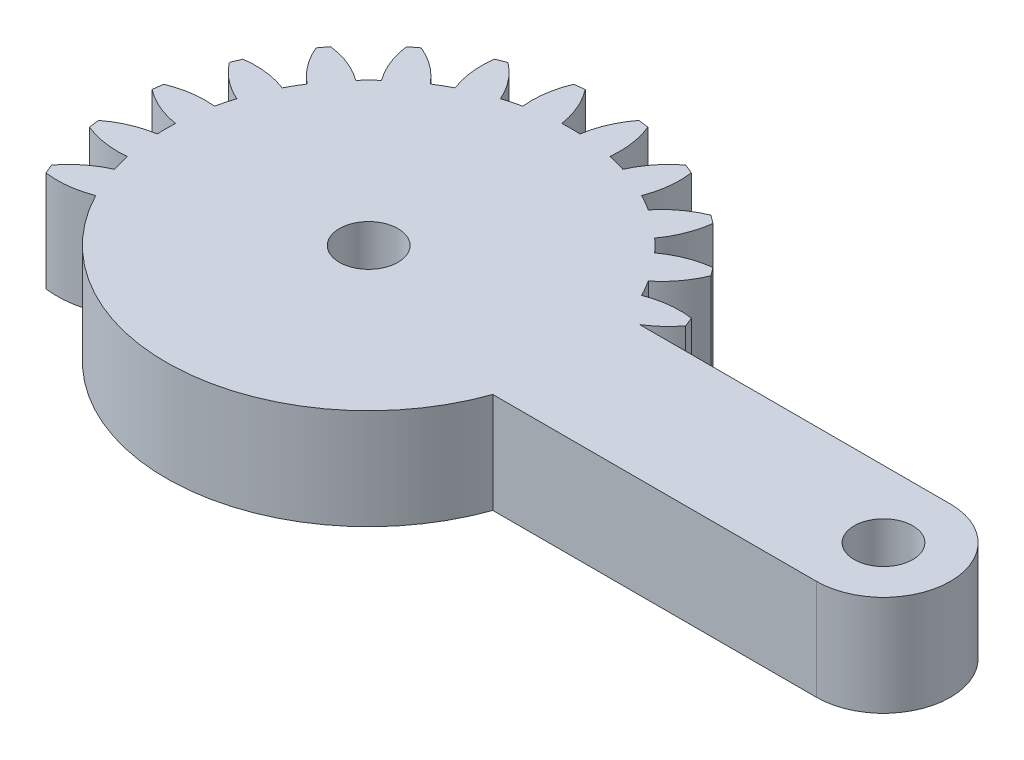
SolidWorks part; units mm, degrees
ref_plane "Front Plane" through (0, 0, 0) normal (0, 0, 1) x (1, 0, 0)
ref_plane "Top Plane" through (0, 0, 0) normal (0, 1, 0) x (1, 0, 0)
ref_plane "Right Plane" through (0, 0, 0) normal (1, 0, 0) x (0, 0, -1)
sketch "Sketch1" plane through (0, 0, 0) normal (0, 1, 0) x (1, 0, 0)
  line L0 (20.6437, 4) -> (2.0816, 4)
  line L1 (2.0816, -4) -> (20.6437, -4)
  arc A0 (2.0816, 4) -> (3.5217, 5.3071) centre (-0.7683, 8.5867) ccw
  arc A1 (3.5217, 5.3071) -> (3.2829, 5.8838) centre (-10.1063, 0) ccw
  arc A2 (3.2829, 5.8838) -> (0.6271, 5.5703) centre (2.5684, 0.5313) ccw
  arc A3 (0.6271, 5.5703) -> (0.0844, 6.5103) centre (-10.1063, 0) ccw
  arc A4 (0.0844, 6.5103) -> (1.6838, 8.6535) centre (-3.3089, 10.711) ccw
  arc A5 (1.6838, 8.6535) -> (1.3038, 9.1487) centre (-10.1063, 0) ccw
  arc A6 (1.3038, 9.1487) -> (-1.1803, 8.1585) centre (1.999, 3.7936) ccw
  arc A7 (-1.1803, 8.1585) -> (-1.9479, 8.926) centre (-10.1063, 0) ccw
  arc A8 (-1.9479, 8.926) -> (-0.9576, 11.4102) centre (-6.3127, 12.1053) ccw
  arc A9 (-0.9576, 11.4102) -> (-1.4528, 11.7901) centre (-10.1063, 0) ccw
  arc A10 (-1.4528, 11.7901) -> (-3.596, 10.1907) centre (0.6046, 6.7975) ccw
  arc A11 (-3.596, 10.1907) -> (-4.5361, 10.7334) centre (-10.1063, 0) ccw
  arc A12 (-4.5361, 10.7334) -> (-4.2225, 13.3892) centre (-9.5751, 12.6747) ccw
  arc A13 (-4.2225, 13.3892) -> (-4.7992, 13.6281) centre (-10.1063, 0) ccw
  arc A14 (-4.7992, 13.6281) -> (-6.4554, 11.5285) centre (-1.5196, 9.3381) ccw
  arc A15 (-6.4554, 11.5285) -> (-7.5039, 11.8094) centre (-10.1063, 0) ccw
  arc A16 (-7.5039, 11.8094) -> (-7.8884, 14.4558) centre (-12.8736, 12.3803) ccw
  arc A17 (-7.8884, 14.4558) -> (-8.5072, 14.5373) centre (-10.1063, 0) ccw
  arc A18 (-8.5072, 14.5373) -> (-9.5636, 12.0806) centre (-4.2291, 11.2423) ccw
  arc A19 (-9.5636, 12.0806) -> (-10.6491, 12.0806) centre (-10.1063, 0) ccw
  arc A20 (-10.6491, 12.0806) -> (-11.7054, 14.5373) centre (-15.9836, 11.2423) ccw
  arc A21 (-11.7054, 14.5373) -> (-12.3243, 14.4558) centre (-10.1063, 0) ccw
  arc A22 (-12.3243, 14.4558) -> (-12.7088, 11.8094) centre (-7.3391, 12.3803) ccw
  arc A23 (-12.7088, 11.8094) -> (-13.7573, 11.5285) centre (-10.1063, 0) ccw
  arc A24 (-13.7573, 11.5285) -> (-15.4135, 13.6281) centre (-18.6931, 9.3381) ccw
  arc A25 (-15.4135, 13.6281) -> (-15.9901, 13.3892) centre (-10.1063, 0) ccw
  arc A26 (-15.9901, 13.3892) -> (-15.6766, 10.7334) centre (-10.6376, 12.6747) ccw
  arc A27 (-15.6766, 10.7334) -> (-16.6166, 10.1907) centre (-10.1063, 0) ccw
  arc A28 (-16.6166, 10.1907) -> (-18.7599, 11.7901) centre (-20.8173, 6.7975) ccw
  arc A29 (-18.7599, 11.7901) -> (-19.255, 11.4102) centre (-10.1063, 0) ccw
  arc A30 (-19.255, 11.4102) -> (-18.2648, 8.926) centre (-13.9, 12.1053) ccw
  arc A31 (-18.2648, 8.926) -> (-19.0324, 8.1585) centre (-10.1063, 0) ccw
  arc A32 (-19.0324, 8.1585) -> (-21.5165, 9.1487) centre (-22.2117, 3.7936) ccw
  arc A33 (-21.5165, 9.1487) -> (-21.8965, 8.6535) centre (-10.1063, 0) ccw
  arc A34 (-21.8965, 8.6535) -> (-20.2971, 6.5103) centre (-16.9038, 10.711) ccw
  arc A35 (-20.2971, 6.5103) -> (-20.8398, 5.5703) centre (-10.1063, 0) ccw
  arc A36 (-20.8398, 5.5703) -> (-23.4956, 5.8838) centre (-22.7811, 0.5313) ccw
  arc A37 (-23.4956, 5.8838) -> (-23.7344, 5.3071) centre (-10.1063, 0) ccw
  arc A38 (-23.7344, 5.3071) -> (-21.6348, 3.6509) centre (-19.4444, 8.5867) ccw
  arc A39 (-21.6348, 3.6509) -> (-21.9157, 2.6025) centre (-10.1063, 0) ccw
  arc A40 (-21.9157, 2.6025) -> (-24.5622, 2.2179) centre (-22.4867, -2.7673) ccw
  arc A41 (-24.5622, 2.2179) -> (-24.6437, 1.5991) centre (-10.1063, 0) ccw
  arc A42 (-24.6437, 1.5991) -> (-22.1869, 0.5427) centre (-21.3486, 5.8773) ccw
  arc A43 (-22.1869, 0.5427) -> (-22.1869, -0.5427) centre (-10.1063, 0) ccw
  arc A44 (-22.1869, -0.5427) -> (-24.6437, -1.5991) centre (-21.3486, -5.8773) ccw
  arc A45 (-24.6437, -1.5991) -> (-24.5622, -2.2179) centre (-10.1063, 0) ccw
  arc A46 (-24.5622, -2.2179) -> (-21.9157, -2.6025) centre (-22.4867, 2.7673) ccw
  arc A47 (-21.9157, -2.6025) -> (-21.6348, -3.6509) centre (-10.1063, 0) ccw
  arc A48 (-21.6348, -3.6509) -> (-23.7344, -5.3071) centre (-19.4444, -8.5867) ccw
  arc A49 (-23.7344, -5.3071) -> (-23.4956, -5.8838) centre (-10.1063, 0) ccw
  arc A50 (-23.4956, -5.8838) -> (-20.8398, -5.5703) centre (-22.7811, -0.5313) ccw
  arc A51 (-20.8398, -5.5703) -> (-20.2971, -6.5103) centre (-10.1063, 0) ccw
  arc A52 (-20.2971, -6.5103) -> (-21.8965, -8.6535) centre (-16.9038, -10.711) ccw
  arc A53 (-21.8965, -8.6535) -> (-21.5165, -9.1487) centre (-10.1063, 0) ccw
  arc A54 (-21.5165, -9.1487) -> (-19.0324, -8.1585) centre (-22.2117, -3.7936) ccw
  arc A55 (-19.0324, -8.1585) -> (-18.2648, -8.926) centre (-10.1063, 0) ccw
  arc A56 (-18.2648, -8.926) -> (-19.255, -11.4102) centre (-13.9, -12.1053) ccw
  arc A57 (-19.255, -11.4102) -> (-18.7599, -11.7901) centre (-10.1063, 0) ccw
  arc A58 (-18.7599, -11.7901) -> (-16.6166, -10.1907) centre (-20.8173, -6.7975) ccw
  arc A59 (-16.6166, -10.1907) -> (-15.6766, -10.7334) centre (-10.1063, 0) ccw
  arc A60 (-15.6766, -10.7334) -> (-15.9901, -13.3892) centre (-10.6376, -12.6747) ccw
  arc A61 (-15.9901, -13.3892) -> (-15.4135, -13.6281) centre (-10.1063, 0) ccw
  arc A62 (-15.4135, -13.6281) -> (-13.7573, -11.5285) centre (-18.6931, -9.3381) ccw
  arc A63 (-13.7573, -11.5285) -> (-12.7088, -11.8094) centre (-10.1063, 0) ccw
  arc A64 (-12.7088, -11.8094) -> (-12.3243, -14.4558) centre (-7.3391, -12.3803) ccw
  arc A65 (-12.3243, -14.4558) -> (-11.7054, -14.5373) centre (-10.1063, 0) ccw
  arc A66 (-11.7054, -14.5373) -> (-10.6491, -12.0806) centre (-15.9836, -11.2423) ccw
  arc A67 (-10.6491, -12.0806) -> (-9.5636, -12.0806) centre (-10.1063, 0) ccw
  arc A68 (-9.5636, -12.0806) -> (-8.5072, -14.5373) centre (-4.2291, -11.2423) ccw
  arc A69 (-8.5072, -14.5373) -> (-7.8884, -14.4558) centre (-10.1063, 0) ccw
  arc A70 (-7.8884, -14.4558) -> (-7.5039, -11.8094) centre (-12.8736, -12.3803) ccw
  arc A71 (-7.5039, -11.8094) -> (-6.4554, -11.5285) centre (-10.1063, 0) ccw
  arc A72 (-6.4554, -11.5285) -> (-4.7992, -13.6281) centre (-1.5196, -9.3381) ccw
  arc A73 (-4.7992, -13.6281) -> (-4.2225, -13.3892) centre (-10.1063, 0) ccw
  arc A74 (-4.2225, -13.3892) -> (-4.5361, -10.7334) centre (-9.5751, -12.6747) ccw
  arc A75 (-4.5361, -10.7334) -> (-3.596, -10.1907) centre (-10.1063, 0) ccw
  arc A76 (-3.596, -10.1907) -> (-1.4528, -11.7901) centre (0.6046, -6.7975) ccw
  arc A77 (-1.4528, -11.7901) -> (-0.9576, -11.4102) centre (-10.1063, 0) ccw
  arc A78 (-0.9576, -11.4102) -> (-1.9479, -8.926) centre (-6.3127, -12.1053) ccw
  arc A79 (-1.9479, -8.926) -> (-1.1803, -8.1585) centre (-10.1063, 0) ccw
  arc A80 (-1.1803, -8.1585) -> (1.3038, -9.1487) centre (1.999, -3.7936) ccw
  arc A81 (1.3038, -9.1487) -> (1.6838, -8.6535) centre (-10.1063, 0) ccw
  arc A82 (1.6838, -8.6535) -> (0.0844, -6.5103) centre (-3.3089, -10.711) ccw
  arc A83 (0.0844, -6.5103) -> (0.6271, -5.5703) centre (-10.1063, 0) ccw
  arc A84 (0.6271, -5.5703) -> (3.2829, -5.8838) centre (2.5684, -0.5313) ccw
  arc A85 (3.2829, -5.8838) -> (3.5217, -5.3071) centre (-10.1063, 0) ccw
  arc A86 (3.5217, -5.3071) -> (2.0816, -4) centre (-0.7683, -8.5867) ccw
  arc A87 (20.6437, -4) -> (20.6437, 4) centre (20.6437, 0) ccw
  circle A88 centre (-10.1063, 0) radius 1.75
  circle A89 centre (20.6437, 0) radius 1.75
  dimension "D1" = 3.5
  dimension "D2" = 3.5
extrude "Boss-Extrude1" add sketch "Sketch1" along normal blind 4
sketch "Sketch2" plane through (0, 4, 0) normal (0, 1, 0) x (1, 0, 0)
  line L0 (2.0816, -4) -> (1.3057, -4)
  line L2 (20.6437, 4) -> (2.0816, 4)
  line L3 (2.0816, -4) -> (20.6437, -4)
  line L4 (20.6437, 4) -> (2.0816, 4)
  line L5 (2.0816, -4) -> (20.6437, -4)
  circle A0 centre (-10.1063, 0) radius 12.0927
  arc A88 (20.6437, -4) -> (20.6437, 4) centre (20.6437, 0) ccw
  arc A89 (2.0816, 4) -> (3.5217, 5.3071) centre (-0.7683, 8.5867) ccw
  arc A90 (3.5217, 5.3071) -> (3.2829, 5.8838) centre (-10.1063, 0) ccw
  arc A91 (3.2829, 5.8838) -> (0.6271, 5.5703) centre (2.5684, 0.5313) ccw
  arc A92 (0.6271, 5.5703) -> (0.0844, 6.5103) centre (-10.1063, 0) ccw
  arc A93 (0.0844, 6.5103) -> (1.6838, 8.6535) centre (-3.3089, 10.711) ccw
  arc A94 (1.6838, 8.6535) -> (1.3038, 9.1487) centre (-10.1063, 0) ccw
  arc A95 (1.3038, 9.1487) -> (-1.1803, 8.1585) centre (1.999, 3.7936) ccw
  arc A96 (-1.1803, 8.1585) -> (-1.9479, 8.926) centre (-10.1063, 0) ccw
  arc A97 (-1.9479, 8.926) -> (-0.9576, 11.4102) centre (-6.3127, 12.1053) ccw
  arc A98 (-0.9576, 11.4102) -> (-1.4528, 11.7901) centre (-10.1063, 0) ccw
  arc A99 (-1.4528, 11.7901) -> (-3.596, 10.1907) centre (0.6046, 6.7975) ccw
  arc A100 (-3.596, 10.1907) -> (-4.5361, 10.7334) centre (-10.1063, 0) ccw
  arc A101 (-4.5361, 10.7334) -> (-4.2225, 13.3892) centre (-9.5751, 12.6747) ccw
  arc A102 (-4.2225, 13.3892) -> (-4.7992, 13.6281) centre (-10.1063, 0) ccw
  arc A103 (-4.7992, 13.6281) -> (-6.4554, 11.5285) centre (-1.5196, 9.3381) ccw
  arc A104 (-6.4554, 11.5285) -> (-7.5039, 11.8094) centre (-10.1063, 0) ccw
  arc A105 (-7.5039, 11.8094) -> (-7.8884, 14.4558) centre (-12.8736, 12.3803) ccw
  arc A106 (-7.8884, 14.4558) -> (-8.5072, 14.5373) centre (-10.1063, 0) ccw
  arc A107 (-8.5072, 14.5373) -> (-9.5636, 12.0806) centre (-4.2291, 11.2423) ccw
  arc A108 (-9.5636, 12.0806) -> (-10.6491, 12.0806) centre (-10.1063, 0) ccw
  arc A109 (-10.6491, 12.0806) -> (-11.7054, 14.5373) centre (-15.9836, 11.2423) ccw
  arc A110 (-11.7054, 14.5373) -> (-12.3243, 14.4558) centre (-10.1063, 0) ccw
  arc A111 (-12.3243, 14.4558) -> (-12.7088, 11.8094) centre (-7.3391, 12.3803) ccw
  arc A112 (-12.7088, 11.8094) -> (-13.7573, 11.5285) centre (-10.1063, 0) ccw
  arc A113 (-13.7573, 11.5285) -> (-15.4135, 13.6281) centre (-18.6931, 9.3381) ccw
  arc A114 (-15.4135, 13.6281) -> (-15.9901, 13.3892) centre (-10.1063, 0) ccw
  arc A115 (-15.9901, 13.3892) -> (-15.6766, 10.7334) centre (-10.6376, 12.6747) ccw
  arc A116 (-15.6766, 10.7334) -> (-16.6166, 10.1907) centre (-10.1063, 0) ccw
  arc A117 (-16.6166, 10.1907) -> (-18.7599, 11.7901) centre (-20.8173, 6.7975) ccw
  arc A118 (-18.7599, 11.7901) -> (-19.255, 11.4102) centre (-10.1063, 0) ccw
  arc A119 (-19.255, 11.4102) -> (-18.2648, 8.926) centre (-13.9, 12.1053) ccw
  arc A120 (-18.2648, 8.926) -> (-19.0324, 8.1585) centre (-10.1063, 0) ccw
  arc A121 (-19.0324, 8.1585) -> (-21.5165, 9.1487) centre (-22.2117, 3.7936) ccw
  arc A122 (-21.5165, 9.1487) -> (-21.8965, 8.6535) centre (-10.1063, 0) ccw
  arc A123 (-21.8965, 8.6535) -> (-20.2971, 6.5103) centre (-16.9038, 10.711) ccw
  arc A124 (-20.2971, 6.5103) -> (-20.8398, 5.5703) centre (-10.1063, 0) ccw
  arc A125 (-20.8398, 5.5703) -> (-23.4956, 5.8838) centre (-22.7811, 0.5313) ccw
  arc A126 (-23.4956, 5.8838) -> (-23.7344, 5.3071) centre (-10.1063, 0) ccw
  arc A127 (-23.7344, 5.3071) -> (-21.6348, 3.6509) centre (-19.4444, 8.5867) ccw
  arc A128 (-21.6348, 3.6509) -> (-21.9157, 2.6025) centre (-10.1063, 0) ccw
  arc A129 (-21.9157, 2.6025) -> (-24.5622, 2.2179) centre (-22.4867, -2.7673) ccw
  arc A130 (-24.5622, 2.2179) -> (-24.6437, 1.5991) centre (-10.1063, 0) ccw
  arc A131 (-24.6437, 1.5991) -> (-22.1869, 0.5427) centre (-21.3486, 5.8773) ccw
  arc A132 (-22.1869, 0.5427) -> (-22.1869, -0.5427) centre (-10.1063, 0) ccw
  arc A133 (-22.1869, -0.5427) -> (-24.6437, -1.5991) centre (-21.3486, -5.8773) ccw
  arc A134 (-24.6437, -1.5991) -> (-24.5622, -2.2179) centre (-10.1063, 0) ccw
  arc A135 (-24.5622, -2.2179) -> (-21.9157, -2.6025) centre (-22.4867, 2.7673) ccw
  arc A136 (-21.9157, -2.6025) -> (-21.6348, -3.6509) centre (-10.1063, 0) ccw
  arc A137 (-21.6348, -3.6509) -> (-23.7344, -5.3071) centre (-19.4444, -8.5867) ccw
  arc A138 (-23.7344, -5.3071) -> (-23.4956, -5.8838) centre (-10.1063, 0) ccw
  arc A139 (-23.4956, -5.8838) -> (-20.8398, -5.5703) centre (-22.7811, -0.5313) ccw
  arc A140 (-20.8398, -5.5703) -> (-20.2971, -6.5103) centre (-10.1063, 0) ccw
  arc A141 (-20.2971, -6.5103) -> (-21.8965, -8.6535) centre (-16.9038, -10.711) ccw
  arc A142 (-21.8965, -8.6535) -> (-21.5165, -9.1487) centre (-10.1063, 0) ccw
  arc A143 (-21.5165, -9.1487) -> (-19.0324, -8.1585) centre (-22.2117, -3.7936) ccw
  arc A144 (-19.0324, -8.1585) -> (-18.2648, -8.926) centre (-10.1063, 0) ccw
  arc A145 (-18.2648, -8.926) -> (-19.255, -11.4102) centre (-13.9, -12.1053) ccw
  arc A146 (-19.255, -11.4102) -> (-18.7599, -11.7901) centre (-10.1063, 0) ccw
  arc A147 (-18.7599, -11.7901) -> (-16.6166, -10.1907) centre (-20.8173, -6.7975) ccw
  arc A148 (-16.6166, -10.1907) -> (-15.6766, -10.7334) centre (-10.1063, 0) ccw
  arc A149 (-15.6766, -10.7334) -> (-15.9901, -13.3892) centre (-10.6376, -12.6747) ccw
  arc A150 (-15.9901, -13.3892) -> (-15.4135, -13.6281) centre (-10.1063, 0) ccw
  arc A151 (-15.4135, -13.6281) -> (-13.7573, -11.5285) centre (-18.6931, -9.3381) ccw
  arc A152 (-13.7573, -11.5285) -> (-12.7088, -11.8094) centre (-10.1063, 0) ccw
  arc A153 (-12.7088, -11.8094) -> (-12.3243, -14.4558) centre (-7.3391, -12.3803) ccw
  arc A154 (-12.3243, -14.4558) -> (-11.7054, -14.5373) centre (-10.1063, 0) ccw
  arc A155 (-11.7054, -14.5373) -> (-10.6491, -12.0806) centre (-15.9836, -11.2423) ccw
  arc A156 (-10.6491, -12.0806) -> (-9.5636, -12.0806) centre (-10.1063, 0) ccw
  arc A157 (-9.5636, -12.0806) -> (-8.5072, -14.5373) centre (-4.2291, -11.2423) ccw
  arc A158 (-8.5072, -14.5373) -> (-7.8884, -14.4558) centre (-10.1063, 0) ccw
  arc A159 (-7.8884, -14.4558) -> (-7.5039, -11.8094) centre (-12.8736, -12.3803) ccw
  arc A160 (-7.5039, -11.8094) -> (-6.4554, -11.5285) centre (-10.1063, 0) ccw
  arc A161 (-6.4554, -11.5285) -> (-4.7992, -13.6281) centre (-1.5196, -9.3381) ccw
  arc A162 (-4.7992, -13.6281) -> (-4.2225, -13.3892) centre (-10.1063, 0) ccw
  arc A163 (-4.2225, -13.3892) -> (-4.5361, -10.7334) centre (-9.5751, -12.6747) ccw
  arc A164 (-4.5361, -10.7334) -> (-3.596, -10.1907) centre (-10.1063, 0) ccw
  arc A165 (-3.596, -10.1907) -> (-1.4528, -11.7901) centre (0.6046, -6.7975) ccw
  arc A166 (-1.4528, -11.7901) -> (-0.9576, -11.4102) centre (-10.1063, 0) ccw
  arc A167 (-0.9576, -11.4102) -> (-1.9479, -8.926) centre (-6.3127, -12.1053) ccw
  arc A168 (-1.9479, -8.926) -> (-1.1803, -8.1585) centre (-10.1063, 0) ccw
  arc A169 (-1.1803, -8.1585) -> (1.3038, -9.1487) centre (1.999, -3.7936) ccw
  arc A170 (1.3038, -9.1487) -> (1.6838, -8.6535) centre (-10.1063, 0) ccw
  arc A171 (1.6838, -8.6535) -> (0.0844, -6.5103) centre (-3.3089, -10.711) ccw
  arc A172 (0.0844, -6.5103) -> (0.6271, -5.5703) centre (-10.1063, 0) ccw
  arc A173 (0.6271, -5.5703) -> (3.2829, -5.8838) centre (2.5684, -0.5313) ccw
  arc A174 (3.2829, -5.8838) -> (3.5217, -5.3071) centre (-10.1063, 0) ccw
  arc A175 (3.5217, -5.3071) -> (2.0816, -4) centre (-0.7683, -8.5867) ccw
  arc A176 (20.6437, -4) -> (20.6437, 4) centre (20.6437, 0) ccw
  arc A177 (2.0816, 4) -> (3.5217, 5.3071) centre (-0.7683, 8.5867) ccw
  arc A178 (3.5217, 5.3071) -> (3.2829, 5.8838) centre (-10.1063, 0) ccw
  arc A179 (3.2829, 5.8838) -> (0.6271, 5.5703) centre (2.5684, 0.5313) ccw
  arc A180 (0.6271, 5.5703) -> (0.0844, 6.5103) centre (-10.1063, 0) ccw
  arc A181 (0.0844, 6.5103) -> (1.6838, 8.6535) centre (-3.3089, 10.711) ccw
  arc A182 (1.6838, 8.6535) -> (1.3038, 9.1487) centre (-10.1063, 0) ccw
  arc A183 (1.3038, 9.1487) -> (-1.1803, 8.1585) centre (1.999, 3.7936) ccw
  arc A184 (-1.1803, 8.1585) -> (-1.9479, 8.926) centre (-10.1063, 0) ccw
  arc A185 (-1.9479, 8.926) -> (-0.9576, 11.4102) centre (-6.3127, 12.1053) ccw
  arc A186 (-0.9576, 11.4102) -> (-1.4528, 11.7901) centre (-10.1063, 0) ccw
  arc A187 (-1.4528, 11.7901) -> (-3.596, 10.1907) centre (0.6046, 6.7975) ccw
  arc A188 (-3.596, 10.1907) -> (-4.5361, 10.7334) centre (-10.1063, 0) ccw
  arc A189 (-4.5361, 10.7334) -> (-4.2225, 13.3892) centre (-9.5751, 12.6747) ccw
  arc A190 (-4.2225, 13.3892) -> (-4.7992, 13.6281) centre (-10.1063, 0) ccw
  arc A191 (-4.7992, 13.6281) -> (-6.4554, 11.5285) centre (-1.5196, 9.3381) ccw
  arc A192 (-6.4554, 11.5285) -> (-7.5039, 11.8094) centre (-10.1063, 0) ccw
  arc A193 (-7.5039, 11.8094) -> (-7.8884, 14.4558) centre (-12.8736, 12.3803) ccw
  arc A194 (-7.8884, 14.4558) -> (-8.5072, 14.5373) centre (-10.1063, 0) ccw
  arc A195 (-8.5072, 14.5373) -> (-9.5636, 12.0806) centre (-4.2291, 11.2423) ccw
  arc A196 (-9.5636, 12.0806) -> (-10.6491, 12.0806) centre (-10.1063, 0) ccw
  arc A197 (-10.6491, 12.0806) -> (-11.7054, 14.5373) centre (-15.9836, 11.2423) ccw
  arc A198 (-11.7054, 14.5373) -> (-12.3243, 14.4558) centre (-10.1063, 0) ccw
  arc A199 (-12.3243, 14.4558) -> (-12.7088, 11.8094) centre (-7.3391, 12.3803) ccw
  arc A200 (-12.7088, 11.8094) -> (-13.7573, 11.5285) centre (-10.1063, 0) ccw
  arc A201 (-13.7573, 11.5285) -> (-15.4135, 13.6281) centre (-18.6931, 9.3381) ccw
  arc A202 (-15.4135, 13.6281) -> (-15.9901, 13.3892) centre (-10.1063, 0) ccw
  arc A203 (-15.9901, 13.3892) -> (-15.6766, 10.7334) centre (-10.6376, 12.6747) ccw
  arc A204 (-15.6766, 10.7334) -> (-16.6166, 10.1907) centre (-10.1063, 0) ccw
  arc A205 (-16.6166, 10.1907) -> (-18.7599, 11.7901) centre (-20.8173, 6.7975) ccw
  arc A206 (-18.7599, 11.7901) -> (-19.255, 11.4102) centre (-10.1063, 0) ccw
  arc A207 (-19.255, 11.4102) -> (-18.2648, 8.926) centre (-13.9, 12.1053) ccw
  arc A208 (-18.2648, 8.926) -> (-19.0324, 8.1585) centre (-10.1063, 0) ccw
  arc A209 (-19.0324, 8.1585) -> (-21.5165, 9.1487) centre (-22.2117, 3.7936) ccw
  arc A210 (-21.5165, 9.1487) -> (-21.8965, 8.6535) centre (-10.1063, 0) ccw
  arc A211 (-21.8965, 8.6535) -> (-20.2971, 6.5103) centre (-16.9038, 10.711) ccw
  arc A212 (-20.2971, 6.5103) -> (-20.8398, 5.5703) centre (-10.1063, 0) ccw
  arc A213 (-20.8398, 5.5703) -> (-23.4956, 5.8838) centre (-22.7811, 0.5313) ccw
  arc A214 (-23.4956, 5.8838) -> (-23.7344, 5.3071) centre (-10.1063, 0) ccw
  arc A215 (-23.7344, 5.3071) -> (-21.6348, 3.6509) centre (-19.4444, 8.5867) ccw
  arc A216 (-21.6348, 3.6509) -> (-21.9157, 2.6025) centre (-10.1063, 0) ccw
  arc A217 (-21.9157, 2.6025) -> (-24.5622, 2.2179) centre (-22.4867, -2.7673) ccw
  arc A218 (-24.5622, 2.2179) -> (-24.6437, 1.5991) centre (-10.1063, 0) ccw
  arc A219 (-24.6437, 1.5991) -> (-22.1869, 0.5427) centre (-21.3486, 5.8773) ccw
  arc A220 (-22.1869, 0.5427) -> (-22.1869, -0.5427) centre (-10.1063, 0) ccw
  arc A221 (-22.1869, -0.5427) -> (-24.6437, -1.5991) centre (-21.3486, -5.8773) ccw
  arc A222 (-24.6437, -1.5991) -> (-24.5622, -2.2179) centre (-10.1063, 0) ccw
  arc A223 (-24.5622, -2.2179) -> (-21.9157, -2.6025) centre (-22.4867, 2.7673) ccw
  arc A224 (-21.9157, -2.6025) -> (-21.6348, -3.6509) centre (-10.1063, 0) ccw
  arc A225 (-21.6348, -3.6509) -> (-23.7344, -5.3071) centre (-19.4444, -8.5867) ccw
  arc A226 (-23.7344, -5.3071) -> (-23.4956, -5.8838) centre (-10.1063, 0) ccw
  arc A227 (-23.4956, -5.8838) -> (-20.8398, -5.5703) centre (-22.7811, -0.5313) ccw
  arc A228 (-20.8398, -5.5703) -> (-20.2971, -6.5103) centre (-10.1063, 0) ccw
  arc A229 (-20.2971, -6.5103) -> (-21.8965, -8.6535) centre (-16.9038, -10.711) ccw
  arc A230 (-21.8965, -8.6535) -> (-21.5165, -9.1487) centre (-10.1063, 0) ccw
  arc A231 (-21.5165, -9.1487) -> (-19.0324, -8.1585) centre (-22.2117, -3.7936) ccw
  arc A232 (-19.0324, -8.1585) -> (-18.2648, -8.926) centre (-10.1063, 0) ccw
  arc A233 (-18.2648, -8.926) -> (-19.255, -11.4102) centre (-13.9, -12.1053) ccw
  arc A234 (-19.255, -11.4102) -> (-18.7599, -11.7901) centre (-10.1063, 0) ccw
  arc A235 (-18.7599, -11.7901) -> (-16.6166, -10.1907) centre (-20.8173, -6.7975) ccw
  arc A236 (-16.6166, -10.1907) -> (-15.6766, -10.7334) centre (-10.1063, 0) ccw
  arc A237 (-15.6766, -10.7334) -> (-15.9901, -13.3892) centre (-10.6376, -12.6747) ccw
  arc A238 (-15.9901, -13.3892) -> (-15.4135, -13.6281) centre (-10.1063, 0) ccw
  arc A239 (-15.4135, -13.6281) -> (-13.7573, -11.5285) centre (-18.6931, -9.3381) ccw
  arc A240 (-13.7573, -11.5285) -> (-12.7088, -11.8094) centre (-10.1063, 0) ccw
  arc A241 (-12.7088, -11.8094) -> (-12.3243, -14.4558) centre (-7.3391, -12.3803) ccw
  arc A242 (-12.3243, -14.4558) -> (-11.7054, -14.5373) centre (-10.1063, 0) ccw
  arc A243 (-11.7054, -14.5373) -> (-10.6491, -12.0806) centre (-15.9836, -11.2423) ccw
  arc A244 (-10.6491, -12.0806) -> (-9.5636, -12.0806) centre (-10.1063, 0) ccw
  arc A245 (-9.5636, -12.0806) -> (-8.5072, -14.5373) centre (-4.2291, -11.2423) ccw
  arc A246 (-8.5072, -14.5373) -> (-7.8884, -14.4558) centre (-10.1063, 0) ccw
  arc A247 (-7.8884, -14.4558) -> (-7.5039, -11.8094) centre (-12.8736, -12.3803) ccw
  arc A248 (-7.5039, -11.8094) -> (-6.4554, -11.5285) centre (-10.1063, 0) ccw
  arc A249 (-6.4554, -11.5285) -> (-4.7992, -13.6281) centre (-1.5196, -9.3381) ccw
  arc A250 (-4.7992, -13.6281) -> (-4.2225, -13.3892) centre (-10.1063, 0) ccw
  arc A251 (-4.2225, -13.3892) -> (-4.5361, -10.7334) centre (-9.5751, -12.6747) ccw
  arc A252 (-4.5361, -10.7334) -> (-3.596, -10.1907) centre (-10.1063, 0) ccw
  arc A253 (-3.596, -10.1907) -> (-1.4528, -11.7901) centre (0.6046, -6.7975) ccw
  arc A254 (-1.4528, -11.7901) -> (-0.9576, -11.4102) centre (-10.1063, 0) ccw
  arc A255 (-0.9576, -11.4102) -> (-1.9479, -8.926) centre (-6.3127, -12.1053) ccw
  arc A256 (-1.9479, -8.926) -> (-1.1803, -8.1585) centre (-10.1063, 0) ccw
  arc A257 (-1.1803, -8.1585) -> (1.3038, -9.1487) centre (1.999, -3.7936) ccw
  arc A258 (1.3038, -9.1487) -> (1.6838, -8.6535) centre (-10.1063, 0) ccw
  arc A259 (1.6838, -8.6535) -> (0.0844, -6.5103) centre (-3.3089, -10.711) ccw
  arc A260 (0.0844, -6.5103) -> (0.6271, -5.5703) centre (-10.1063, 0) ccw
  arc A261 (0.6271, -5.5703) -> (3.2829, -5.8838) centre (2.5684, -0.5313) ccw
  arc A262 (3.2829, -5.8838) -> (3.5217, -5.3071) centre (-10.1063, 0) ccw
  arc A263 (3.5217, -5.3071) -> (2.0816, -4) centre (-0.7683, -8.5867) ccw
  dimension "D1" = 0
extrude "Cut-Extrude1" cut sketch "Sketch2" against normal blind 10 contours A230 A231 A0 A229 | A234 A235 A0 A233 | A238 A239 A0 A237 | A242 A243 A0 A241 | A246 A247 A0 A245 | A250 A251 A0 A249 | A254 A255 A0 A253 | A258 A259 A0 A257 | A262 A263 L0 A0 A261
other "Move Face1" face at (20.6437, 0, 1.75) parameters "D1"=2
sketch "Sketch3" plane through (0, 4, 0) normal (0, 1, 0) x (1, 0, 0)
  circle A0 centre (-10.1063, 0) radius 13.45 construction
  circle A1 centre (-10.1063, 0) radius 13.45
